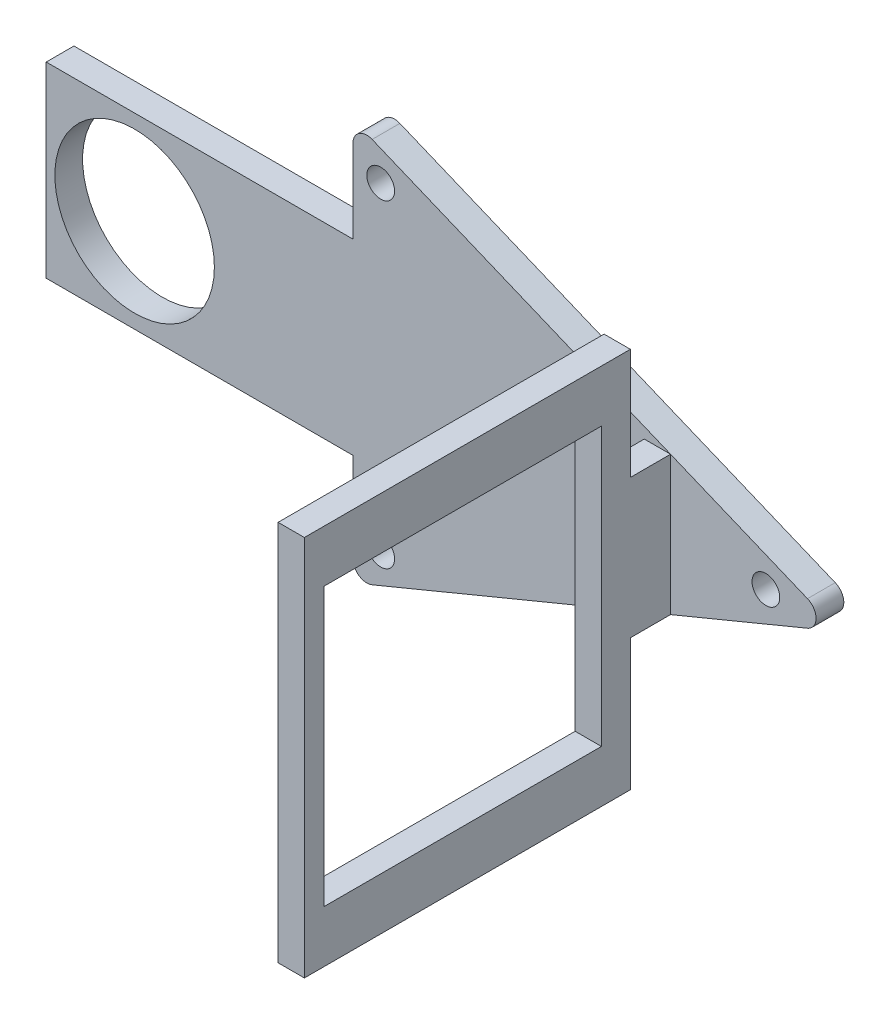
SolidWorks part; units mm, degrees
ref_plane "Ön Düzlem" through (0, 0, 0) normal (0, 0, 1) x (1, 0, 0)
ref_plane "Üst Düzlem" through (0, 0, 0) normal (0, 1, 0) x (1, 0, 0)
ref_plane "Sağ Düzlem" through (0, 0, 0) normal (1, 0, 0) x (0, 0, -1)
ref_plane "Düzlem1" through (0, 0, 4) normal (0, 0, 1) x (1, 0, 0)
sketch "Çizim1" plane through (0, 0, 4) normal (0, 0, 1) x (1, 0, 0)
  line L0 (-27.1468, 25.956) -> (-27.1468, -25.956)
  line L1 (-24.3825, -27.8042) -> (38.3839, -1.8482)
  line L2 (38.3839, 1.8482) -> (-24.3825, 27.8042)
  arc A0 (-27.1468, -25.956) -> (-24.3825, -27.8042) centre (-25.1468, -25.956) ccw
  arc A1 (38.3839, -1.8482) -> (38.3839, 1.8482) centre (37.6196, 0) ccw
  arc A2 (-24.3825, 27.8042) -> (-27.1468, 25.956) centre (-25.1468, 25.956) ccw
extrude "Yükseklik-Ekstrüzyon1" add sketch "Çizim1" against normal blind 4
sketch "Çizim2" plane through (-27.1468, 0, 0) normal (-1, 0, 0) x (0, 0, 1)
  line L0 (4, 13.976) -> (4, -13.024)
  line L1 (4, -13.024) -> (0, -13.024)
  line L2 (0, -13.024) -> (0, 13.976)
  line L3 (0, 13.976) -> (4, 13.976)
extrude "Yükseklik-Ekstrüzyon2" add sketch "Çizim2" along normal blind 44.2214
ref_plane "Düzlem2" through (0, 0, 56.7927) normal (0, 0, 1) x (1, 0, 0)
sketch "Çizim3" plane through (0, 0, 56.7927) normal (0, 0, 1) x (1, 0, 0)
  line L0 (18.6438, -10.0114) -> (18.6438, 10.0114)
  line L1 (18.6438, 10.0114) -> (14.8532, 10.0114)
  line L2 (14.8532, 10.0114) -> (14.8532, -10.0114)
  line L3 (14.8532, -10.0114) -> (18.6438, -10.0114)
extrude "Yükseklik-Ekstrüzyon3" add sketch "Çizim3" against normal up to next
sketch "Çizim4" plane through (0, 10.0114, 0) normal (0, 1, 0) x (-1, 0, 0)
  line L0 (-14.8532, 56.7927) -> (-14.8532, 9.7927)
  line L1 (-14.8532, 9.7927) -> (-18.6438, 9.7927)
  line L2 (-18.6438, 9.7927) -> (-18.6438, 56.7927)
  line L3 (-18.6438, 56.7927) -> (-14.8532, 56.7927)
extrude "Yükseklik-Ekstrüzyon4" add sketch "Çizim4" along normal blind 16
sketch "Çizim5" plane through (0, -10.0114, 0) normal (0, -1, 0) x (1, 0, 0)
  line L0 (14.8532, 9.7927) -> (14.8532, 56.7927)
  line L1 (14.8532, 56.7927) -> (18.6438, 56.7927)
  line L2 (18.6438, 56.7927) -> (18.6438, 9.7927)
  line L3 (18.6438, 9.7927) -> (14.8532, 9.7927)
extrude "Yükseklik-Ekstrüzyon5" add sketch "Çizim5" along normal blind 18.9772
sketch "Çizim6" plane through (18.6438, 0, 0) normal (1, 0, 0) x (0, 0, -1)
  line L0 (-53.9686, 18.5114) -> (-53.9686, -21.4886)
  line L1 (-53.9686, -21.4886) -> (-13.9686, -21.4886)
  line L2 (-13.9686, -21.4886) -> (-13.9686, 18.5114)
  line L3 (-13.9686, 18.5114) -> (-53.9686, 18.5114)
extrude "Kes-Ekstrüzyon1" cut sketch "Çizim6" against normal through all
hole_wizard "Ø23.0 (23) Çap Delik1" positions "Çizim8" profile "Çizim7" hole size "Ø23.0" standard "ANSI Metric"
sketch "Çizim8" plane through (0, 0, 4) normal (0, 0, 1) x (1, 0, 0)
  point P0 (-58.6254, 0.476)
sketch "Çizim7" plane through (-58.6254, 0.476, 4) normal (1, 0, 0) x (0, -1, 0)
  line L0 (0, 0) -> (0, 4)
  line L1 (0, 4) -> (11.5, 4)
  line L2 (11.5, 4) -> (11.5, 0)
  line L5 (11.5, 0) -> (0, 0)
  line L11 (0, -6.35) -> (0, 107.95) construction
  dimension "Thru Hole Dia." = 23
  dimension "Thru Hole Depth" = 4
hole_wizard "Ø4.0 (4) Çap Delik1" positions "Çizim10" profile "Çizim9" hole size "Ø4.0" standard "ANSI Metric"
sketch "Çizim10" plane through (0, 0, 0) normal (0, 0, -1) x (-1, 0, 0)
  point P0 (23.1468, -22.9647)
  point P1 (23.1468, 22.9647)
  point P2 (-32.386, 0)
sketch "Çizim9" plane through (-23.1468, -22.9647, 0) normal (1, 0, 0) x (0, 1, 0)
  line L0 (0, 0) -> (0, 56.7927)
  line L1 (0, 56.7927) -> (2, 56.7927)
  line L2 (2, 56.7927) -> (2, 0)
  line L5 (2, 0) -> (0, 0)
  line L11 (0, -6.35) -> (0, 107.95) construction
  dimension "Thru Hole Dia." = 4
  dimension "Thru Hole Depth" = 56.7927
